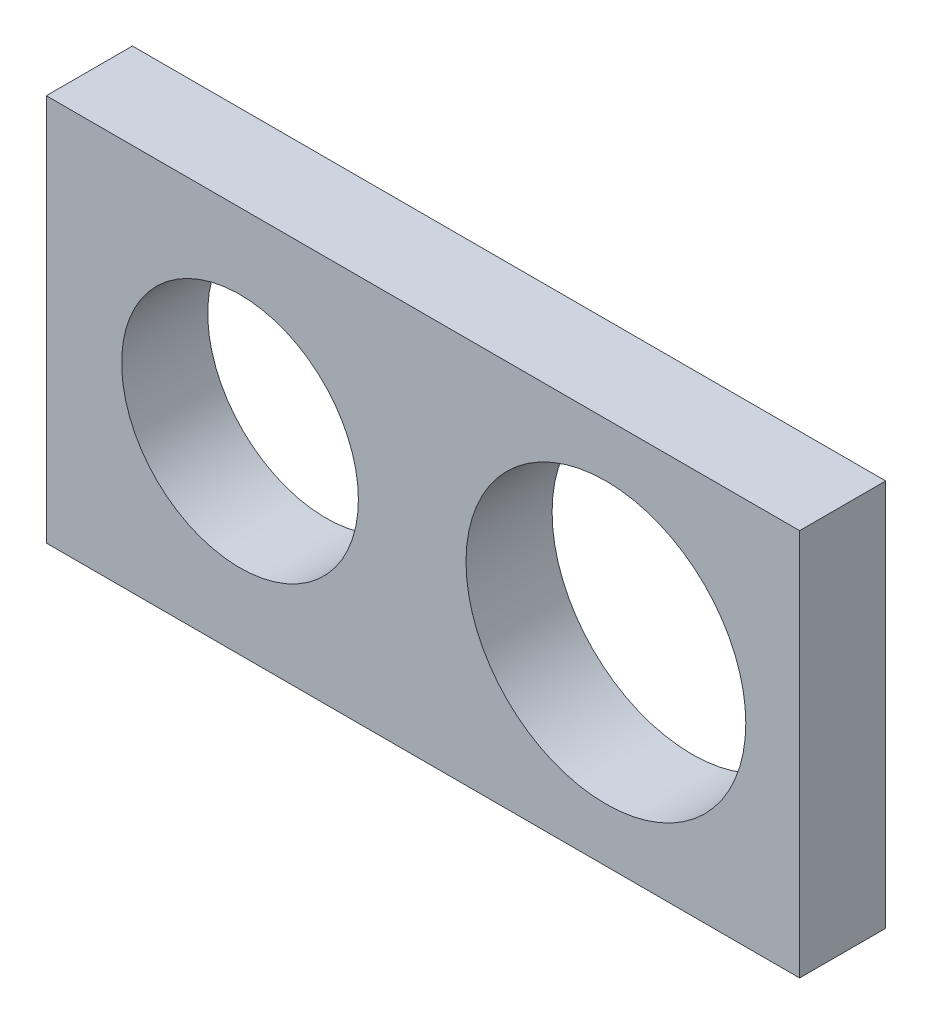
SolidWorks part; units mm, degrees
ref_plane "Спереди" through (0, 0, 0) normal (0, 0, 1) x (1, 0, 0)
ref_plane "Сверху" through (0, 0, 0) normal (0, 1, 0) x (1, 0, 0)
ref_plane "Справа" through (0, 0, 0) normal (1, 0, 0) x (0, 0, -1)
sketch "Эскиз1" plane through (0, 0, 0) normal (0, 0, 1) x (1, 0, 0)
  line L0 (-35, -18) -> (35, -18)
  line L1 (35, -18) -> (35, 18)
  line L2 (35, 18) -> (-35, 18)
  line L3 (-35, 18) -> (-35, -18)
extrude "Coupon" add sketch "Эскиз1" along normal blind 8
sketch "Эскиз2" plane through (0, 0, 0) normal (0, 0, 1) x (1, 0, 0)
  circle A0 centre (-17, 0) radius 11
  circle A1 centre (17, 0) radius 13
extrude "Coupon_bores" cut sketch "Эскиз2" against normal mid plane 30
